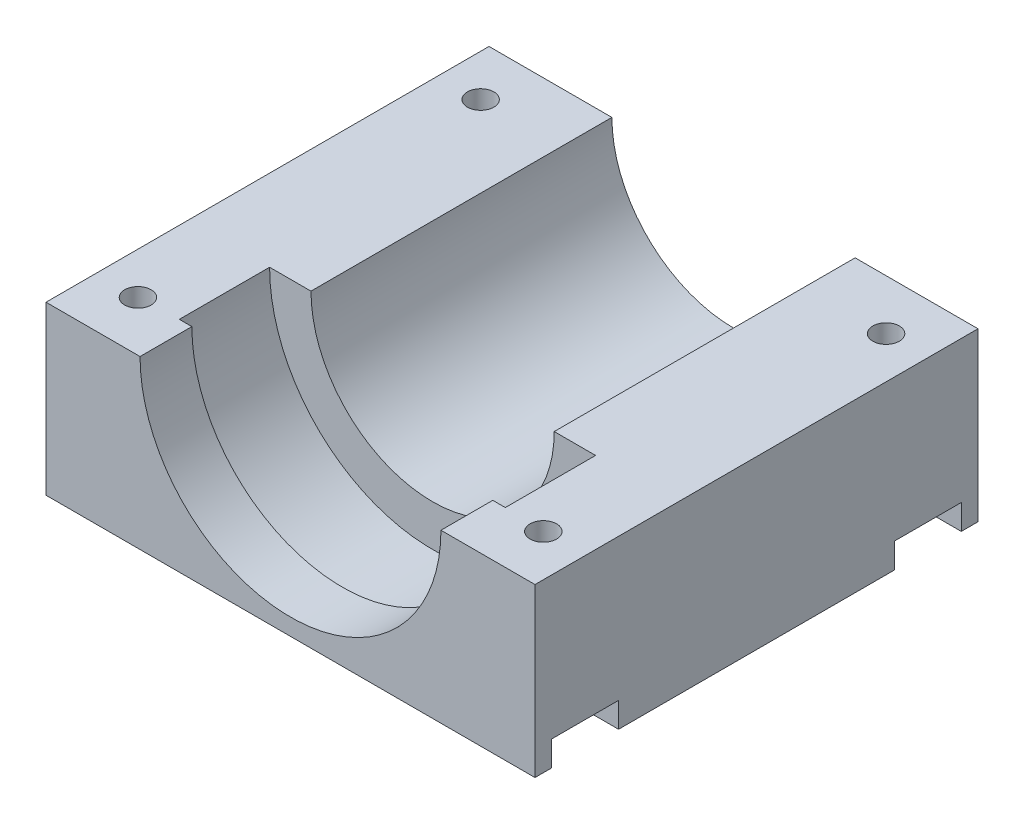
SolidWorks part; units mm, degrees
ref_plane "Alzado" through (0, 0, 0) normal (0, 0, 1) x (1, 0, 0)
ref_plane "Planta" through (0, 0, 0) normal (0, 1, 0) x (1, 0, 0)
ref_plane "Vista lateral" through (0, 0, 0) normal (1, 0, 0) x (0, 0, -1)
sketch "Sketch1" plane through (0, 0, 0) normal (0, 0, 1) x (1, 0, 0)
  line L1 (0, -13.6092) -> (58.5, -13.6092)
  line L2 (0, -13.6092) -> (0, 6.3908)
  line L3 (0, 6.3908) -> (58.5, 6.3908)
  line L4 (58.5, -13.6092) -> (58.5, 6.3908)
  dimension "D1" = 58.5
  dimension "D2" = 20
extrude "Boss-Extrude1" add sketch "Sketch1" along normal blind 53
sketch "Sketch3" plane through (0, 0, 53) normal (0, 0, 1) x (1, 0, 0)
  line L0 (11.25, 6.3908) -> (47.25, 6.3908)
  arc A0 (11.25, 6.3908) -> (47.25, 6.3908) centre (29.25, 6.3908) ccw
  dimension "D3" = 18
extrude "Cut-Extrude2" cut sketch "Sketch3" against normal blind 17
ref_plane "Plane1" through (11.25, 6.3908, 36) normal (-1, 0, 0) x (0, 0, 1)
sketch "Sketch5" plane through (0, 0, 0) normal (0, 0, -1) x (-1, 0, 0)
  line L4 (-43.8, 6.3908) -> (-14.7, 6.3908)
  arc A1 (-43.8, 6.3908) -> (-14.7, 6.3908) centre (-29.25, 6.3908) ccw
  dimension "D3" = 14.55
extrude "Cut-Extrude3" cut sketch "Sketch5" against normal blind 42.5
sketch "Sketch6" plane through (0, 0, 53) normal (0, 0, 1) x (1, 0, 0)
  line L0 (58.5, 2.6291) -> (49, 2.6291)
  line L1 (58.5, -13.6092) -> (58.5, 6.3908) construction
  line L2 (0, 2.6291) -> (9.5, 2.6291)
  line L3 (58.5, 2.6291) -> (58.5, -13.6092)
  line L4 (58.5, -13.6092) -> (0, -13.6092)
  line L5 (0, -13.6092) -> (0, 2.6291)
  arc A0 (49, 2.6291) -> (9.5, 2.6291) centre (29.25, 7.7188) cw
  dimension "D1" = 9.5
  dimension "D2" = 9.5
sketch "Sketch8" plane through (0, -13.6092, 0) normal (0, -1, 0) x (-1, 0, 0)
  line L0 (-58.5, -53) -> (-58.5, 0) construction
  line L1 (-58.5, -2) -> (-48.5, -2)
  line L2 (-58.5, -2) -> (-58.5, -10)
  line L3 (-58.5, -10) -> (-48.5, -10)
  line L4 (-48.5, -2) -> (-48.5, -10)
  line L5 (0, 0) -> (-58.5, 0) construction
  dimension "D1" = 8
  dimension "D2" = 2
  dimension "D4" = 0
extrude "Cut-Extrude6" cut sketch "Sketch8" against normal blind 3
sketch "Sketch7" plane through (0, -13.6092, 0) normal (0, -1, 0) x (-1, 0, 0)
  line L0 (-58.5, -53) -> (0, -53) construction
  line L1 (0, 0) -> (-58.5, 0) construction
  line L2 (-58.5, -2) -> (-58.5, -10) construction
  line L3 (0, -53) -> (0, 0) construction
  line L4 (-58.5, -53) -> (-58.5, -10) construction
  circle A0 centre (-53.5, -47) radius 1.585
  circle A1 centre (-53.5, -6) radius 1.585
  circle A2 centre (-5, -6) radius 1.585
  circle A3 centre (-5, -47) radius 1.585
  dimension "D1" = 3.17
  dimension "D2" = 3.17
  dimension "D3" = 3.17
  dimension "D4" = 3.17
  dimension "D5" = 6
  dimension "D6" = 6
  dimension "D7" = 6
  dimension "D8" = 6
  dimension "D9" = 5
  dimension "D10" = 5
  dimension "D11" = 5
  dimension "D12" = 5
extrude "Cut-Extrude5" cut sketch "Sketch7" against normal blind 92.5
ref_plane "Plane2" through (29.25, 0, 0) normal (-1, 0, 0) x (0, 0, 1)
ref_plane "Plane3" through (0, 0, 26.5) normal (0, 0, 1) x (1, 0, 0)
mirror "Mirror1" about plane through (0, 0, 26.5) normal (0, 0, 1) of "Cut-Extrude6" second plane through (29.25, 0, 0) second plane normal (-1, 0, 0)
sketch "Sketch9" plane through (0, 6.3908, 0) normal (0, 1, 0) x (1, 0, 0)
  line L0 (14.7, -36) -> (14.7, -46.8) construction
  line L1 (9.75, -46.8) -> (48.75, -46.8) construction
  point P2 (29.25, -46.8)
  dimension "D1" = 10.8
  dimension "D2" = 39
sketch "Sketch10" plane through (0, 0, 0) normal (0, 0, -1) x (-1, 0, 0)
  line L0 (-9.75, 6.3908) -> (-48.75, 6.3908)
  arc A0 (-9.75, 6.3908) -> (-48.75, 6.3908) centre (-29.25, 6.3908) cw
sketch "Sketch11" plane through (0, 0, 36) normal (0, 0, 1) x (1, 0, 0)
  line L0 (9.75, 6.3908) -> (48.75, 6.3908)
  arc A0 (9.75, 6.3908) -> (48.75, 6.3908) centre (29.25, 6.3908) ccw
extrude "Cut-Extrude7" cut sketch "Sketch11" along normal blind 10.8
